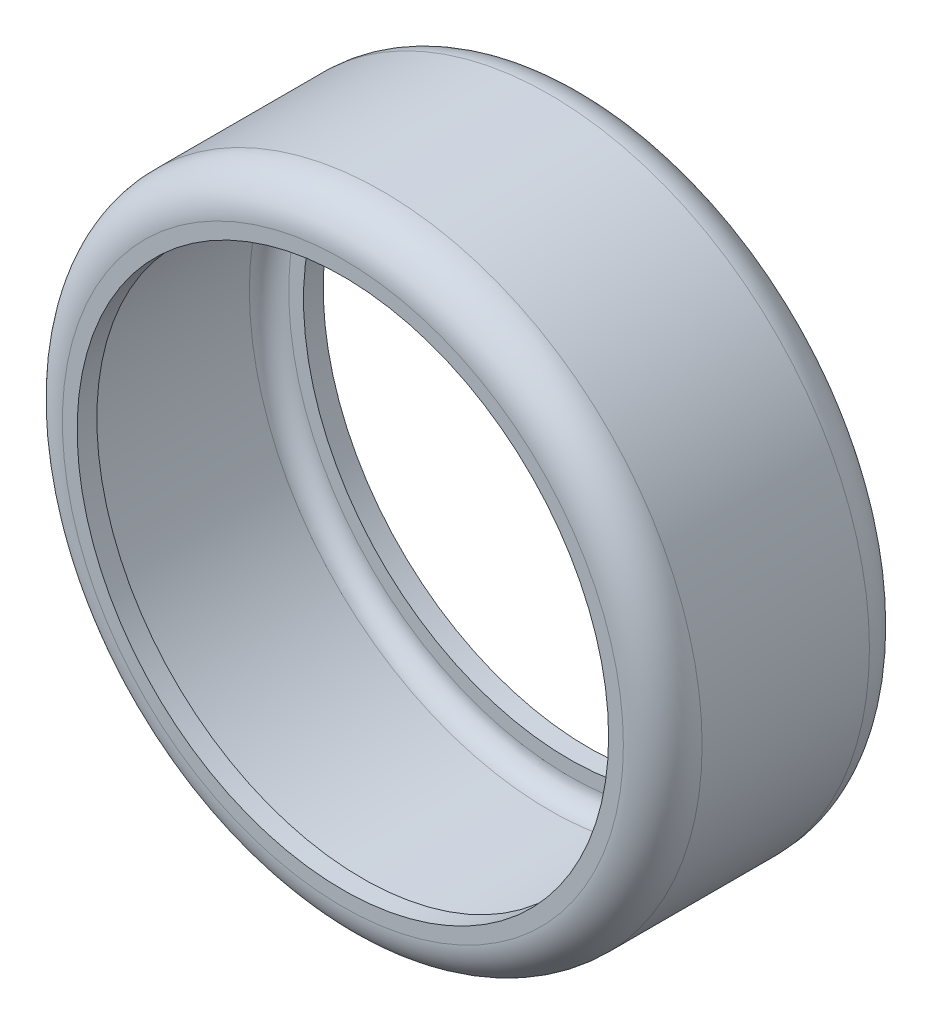
SolidWorks part; units mm, degrees
ref_plane "Спереди" through (0, 0, 0) normal (0, 0, 1) x (1, 0, 0)
ref_plane "Сверху" through (0, 0, 0) normal (0, 1, 0) x (1, 0, 0)
ref_plane "Справа" through (0, 0, 0) normal (1, 0, 0) x (0, 0, -1)
sketch "Эскиз1" plane through (0, 0, 0) normal (0, 0, 1) x (1, 0, 0)
  circle A0 centre (0, 0) radius 54
  dimension "D1" = 108
extrude "Вытянуть-Тонкостенный1" add sketch "Эскиз1" along normal blind 50 thin
fillet "Скругление1" radius 8 2 edges at (65, 0, 0) (65, 0, 50)
shell "Оболочка1" thickness 4
